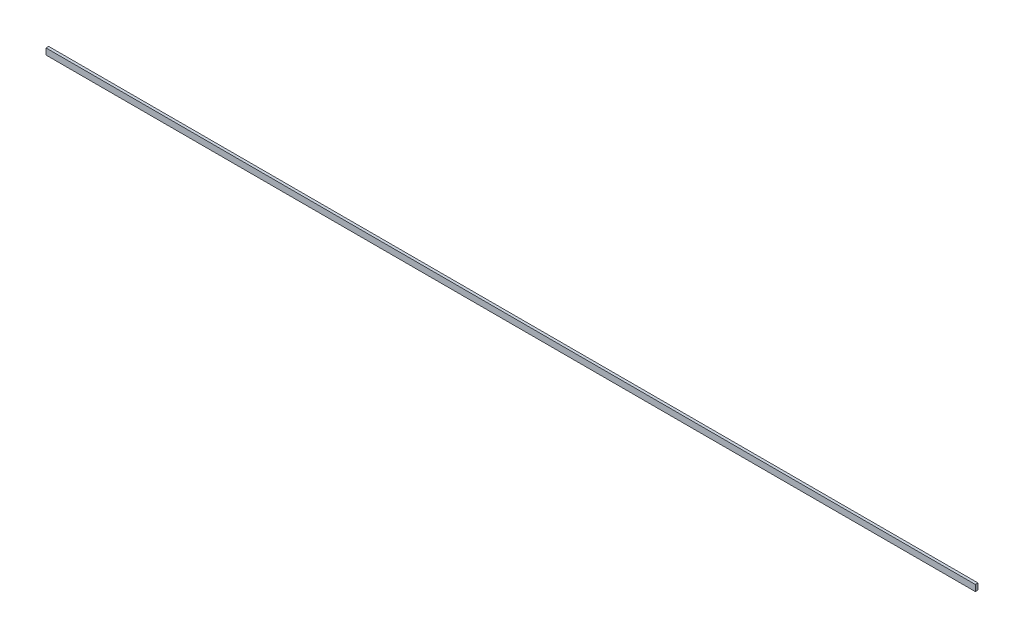
SolidWorks part; units mm, degrees
ref_plane "前视基准面" through (0, 0, 0) normal (0, 0, 1) x (1, 0, 0)
ref_plane "上视基准面" through (0, 0, 0) normal (0, 1, 0) x (1, 0, 0)
ref_plane "右视基准面" through (0, 0, 0) normal (1, 0, 0) x (0, 0, -1)
sketch "草图1" plane through (0, 0, 0) normal (0, 0, 1) x (1, 0, 0)
  line L1 (0, 0) -> (525.1, 0)
  line L2 (0, 0) -> (0, -3.5)
  line L3 (0, -3.5) -> (525.1, -3.5)
  line L4 (525.1, 0) -> (525.1, -3.5)
  dimension "D1" = 3.5
  dimension "D2" = 525.1
extrude "凸台-拉伸1" add sketch "草图1" along normal blind 1.5
